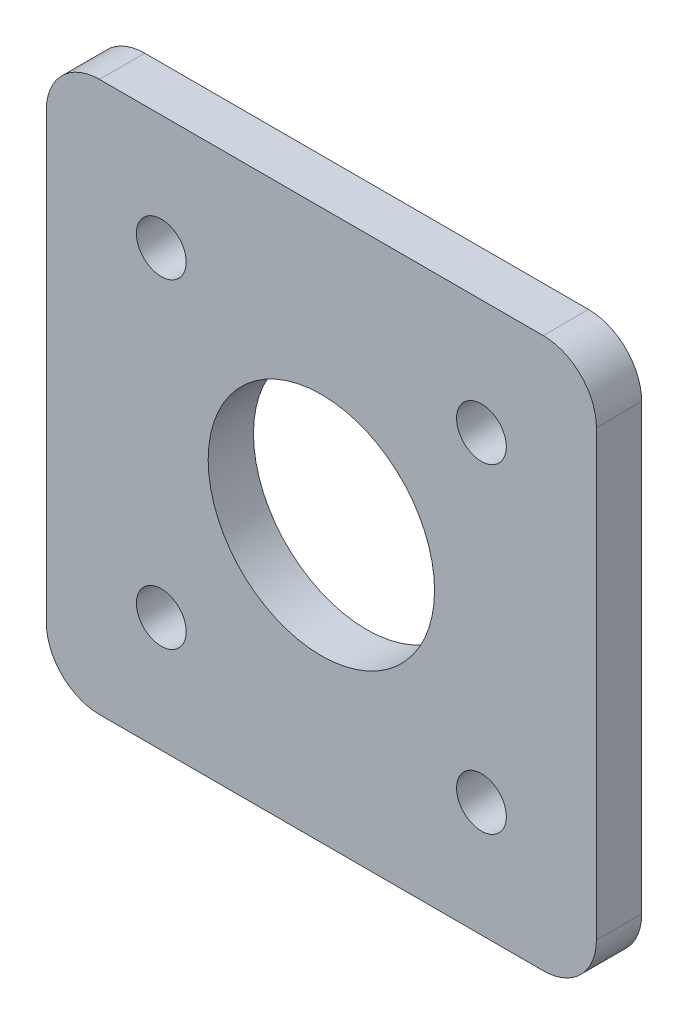
SolidWorks part; units mm, degrees
material "Thornel Mat VMA"
ref_plane "Alzado" through (0, 0, 0) normal (0, 0, 1) x (1, 0, 0)
ref_plane "Planta" through (0, 0, 0) normal (0, 1, 0) x (1, 0, 0)
ref_plane "Vista lateral" through (0, 0, 0) normal (1, 0, 0) x (0, 0, -1)
sketch "Croquis1" plane through (0, 0, 0) normal (0, 0, 1) x (1, 0, 0)
  line L4 (-64.7405, 32.7319) -> (-64.7405, 13.1319)
  line L5 (-62.0405, 10.4319) -> (-42.4405, 10.4319)
  line L6 (-39.7405, 13.1319) -> (-39.7405, 32.7319)
  line L7 (-42.4405, 35.4319) -> (-62.0405, 35.4319)
  circle A9 centre (-45.1694, 30.0029) radius 1.1
  circle A10 centre (-52.2405, 22.9319) radius 3
  circle A11 centre (-45.1694, 15.8608) radius 1.1
  circle A12 centre (-59.3115, 15.8608) radius 1.1
  circle A13 centre (-59.3115, 30.0029) radius 1.1
  arc A14 (-64.7405, 13.1319) -> (-62.0405, 10.4319) centre (-62.0405, 13.1319) ccw
  arc A15 (-42.4405, 10.4319) -> (-39.7405, 13.1319) centre (-42.4405, 13.1319) ccw
  arc A16 (-39.7405, 32.7319) -> (-42.4405, 35.4319) centre (-42.4405, 32.7319) ccw
  arc A17 (-62.0405, 35.4319) -> (-64.7405, 32.7319) centre (-62.0405, 32.7319) ccw
extrude "Saliente-Extruir1" add sketch "Croquis1" along normal blind 2
sketch "Croquis2" plane through (0, 0, 2) normal (0, 0, 1) x (1, 0, 0)
  line L4 (-64.3905, 32.7319) -> (-64.3905, 13.1319)
  line L5 (-62.0405, 10.7819) -> (-42.4405, 10.7819)
  line L6 (-40.0905, 13.1319) -> (-40.0905, 32.7319)
  line L7 (-42.4405, 35.0819) -> (-62.0405, 35.0819)
  line L8 (-64.7405, 32.7319) -> (-64.7405, 13.1319)
  line L9 (-62.0405, 10.4319) -> (-42.4405, 10.4319)
  line L10 (-39.7405, 13.1319) -> (-39.7405, 32.7319)
  line L11 (-42.4405, 35.4319) -> (-62.0405, 35.4319)
  line L12 (-64.7405, 32.7319) -> (-64.7405, 13.1319)
  line L13 (-62.0405, 10.4319) -> (-42.4405, 10.4319)
  line L14 (-39.7405, 13.1319) -> (-39.7405, 32.7319)
  line L15 (-42.4405, 35.4319) -> (-62.0405, 35.4319)
  arc A4 (-62.0405, 35.0819) -> (-64.3905, 32.7319) centre (-62.0405, 32.7319) ccw
  arc A5 (-64.3905, 13.1319) -> (-62.0405, 10.7819) centre (-62.0405, 13.1319) ccw
  arc A6 (-42.4405, 10.7819) -> (-40.0905, 13.1319) centre (-42.4405, 13.1319) ccw
  arc A7 (-40.0905, 32.7319) -> (-42.4405, 35.0819) centre (-42.4405, 32.7319) ccw
  arc A8 (-62.0405, 35.4319) -> (-64.7405, 32.7319) centre (-62.0405, 32.7319) ccw
  arc A9 (-64.7405, 13.1319) -> (-62.0405, 10.4319) centre (-62.0405, 13.1319) ccw
  arc A10 (-42.4405, 10.4319) -> (-39.7405, 13.1319) centre (-42.4405, 13.1319) ccw
  arc A11 (-39.7405, 32.7319) -> (-42.4405, 35.4319) centre (-42.4405, 32.7319) ccw
  arc A12 (-62.0405, 35.4319) -> (-64.7405, 32.7319) centre (-62.0405, 32.7319) ccw
  arc A13 (-64.7405, 13.1319) -> (-62.0405, 10.4319) centre (-62.0405, 13.1319) ccw
  arc A14 (-42.4405, 10.4319) -> (-39.7405, 13.1319) centre (-42.4405, 13.1319) ccw
  arc A15 (-39.7405, 32.7319) -> (-42.4405, 35.4319) centre (-42.4405, 32.7319) ccw
  dimension "D1" = 0
  dimension "D2" = 0.35
extrude "Cortar-Extruir1" cut sketch "Croquis2" against normal up to vertex (2 mm away)
sketch "Croquis3" plane through (0, 0, 2) normal (0, 0, 1) x (1, 0, 0)
  circle A0 centre (-52.2405, 22.9319) radius 5
extrude "Cortar-Extruir2" cut sketch "Croquis3" against normal up to vertex (2 mm away)
